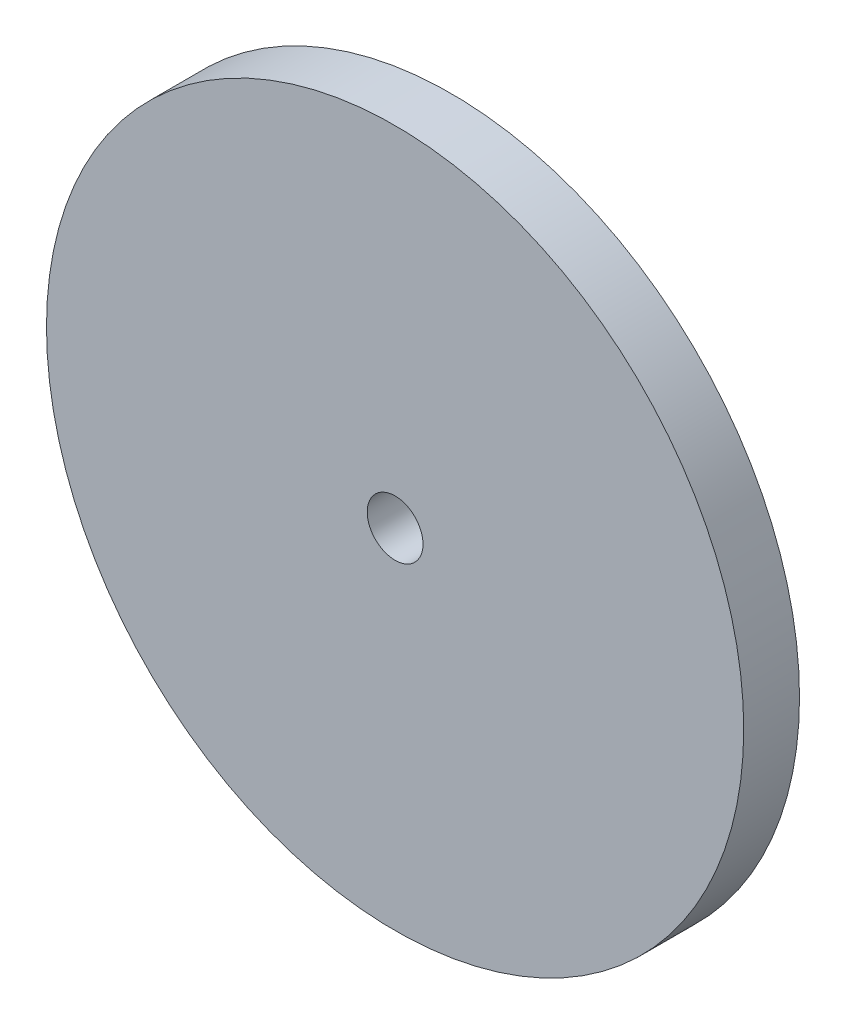
SolidWorks part; units mm, degrees
material "PBT 一般用途"
ref_plane "前视基准面" through (0, 0, 0) normal (0, 0, 1) x (1, 0, 0)
ref_plane "上视基准面" through (0, 0, 0) normal (0, 1, 0) x (1, 0, 0)
ref_plane "右视基准面" through (0, 0, 0) normal (1, 0, 0) x (0, 0, -1)
sketch "草图1" plane through (0, 0, 0) normal (0, 0, 1) x (1, 0, 0)
  circle A0 centre (0, 0) radius 125
  circle A1 centre (0, 0) radius 10
  dimension "D1" = 250
  dimension "D2" = 20
extrude "凸台-拉伸1" add sketch "草图1" along normal blind 20
